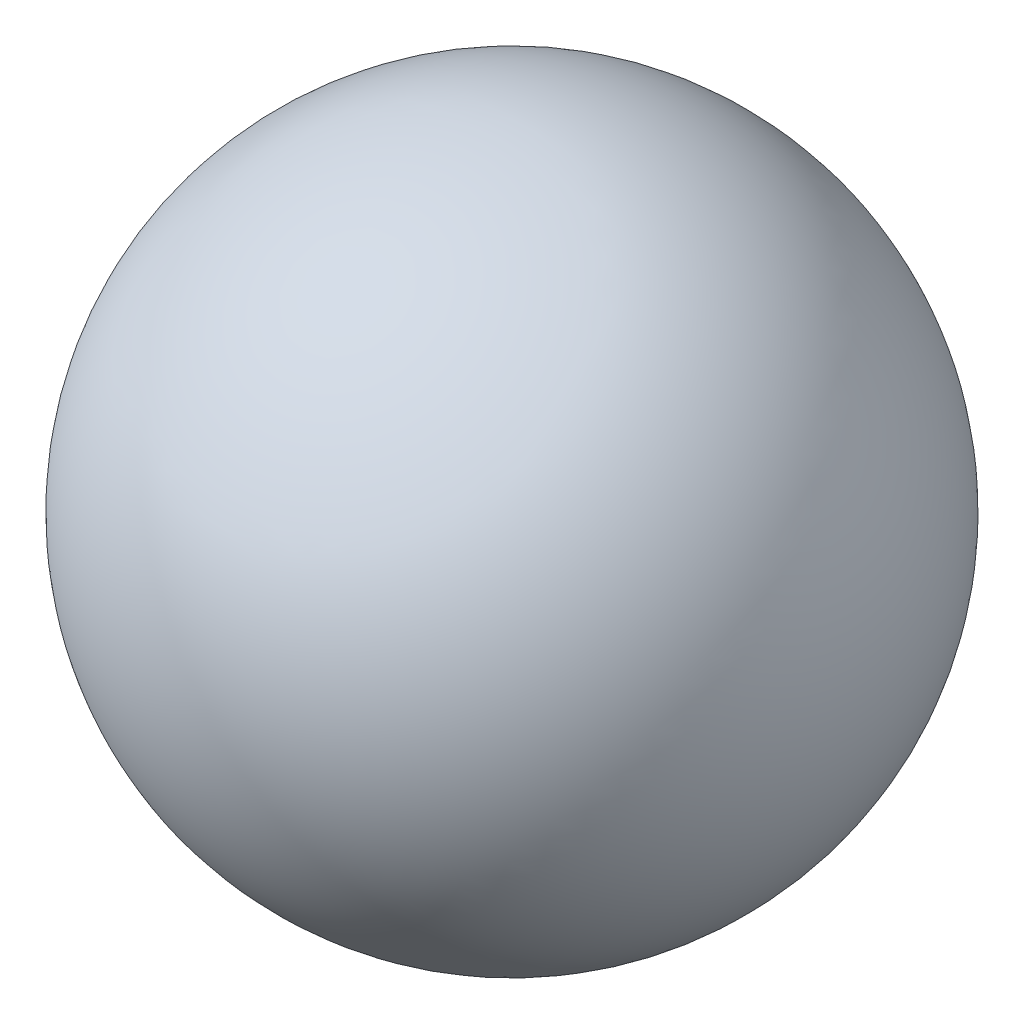
SolidWorks part; units mm, degrees
ref_plane "Front Plane" through (0, 0, 0) normal (0, 0, 1) x (1, 0, 0)
ref_plane "Top Plane" through (0, 0, 0) normal (0, 1, 0) x (1, 0, 0)
ref_plane "Right Plane" through (0, 0, 0) normal (1, 0, 0) x (0, 0, -1)
sketch "Sketch1" plane through (0, 0, 0) normal (0, 1, 0) x (1, 0, 0)
  line L0 (0, 127) -> (0, -127)
  arc A0 (0, -127) -> (0, 127) centre (0, 0) ccw
  dimension "D1" = 254
revolve "Revolve1" add sketch "Sketch1" angle 360 about L0
